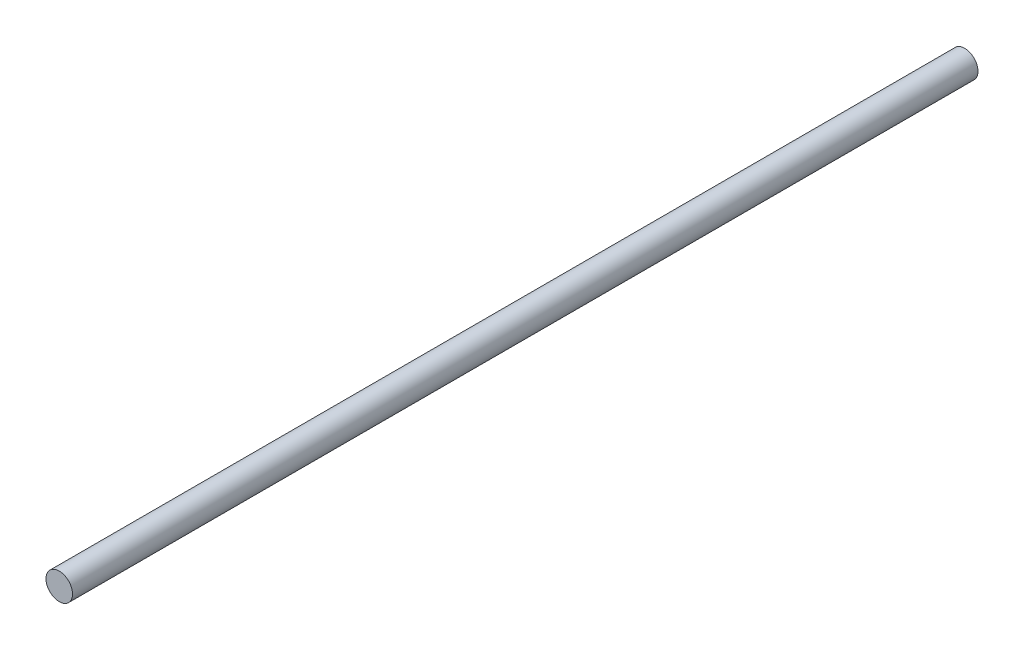
SolidWorks part; units mm, degrees
ref_plane "前视基准面" through (0, 0, 0) normal (0, 0, 1) x (1, 0, 0)
ref_plane "上视基准面" through (0, 0, 0) normal (0, 1, 0) x (1, 0, 0)
ref_plane "右视基准面" through (0, 0, 0) normal (1, 0, 0) x (0, 0, -1)
sketch "草图1" plane through (0, 0, 0) normal (0, 0, 1) x (1, 0, 0)
  circle A0 centre (0, 0) radius 3
  dimension "D1" = 6
extrude "凸台-拉伸1" add sketch "草图1" along normal blind 204.7
